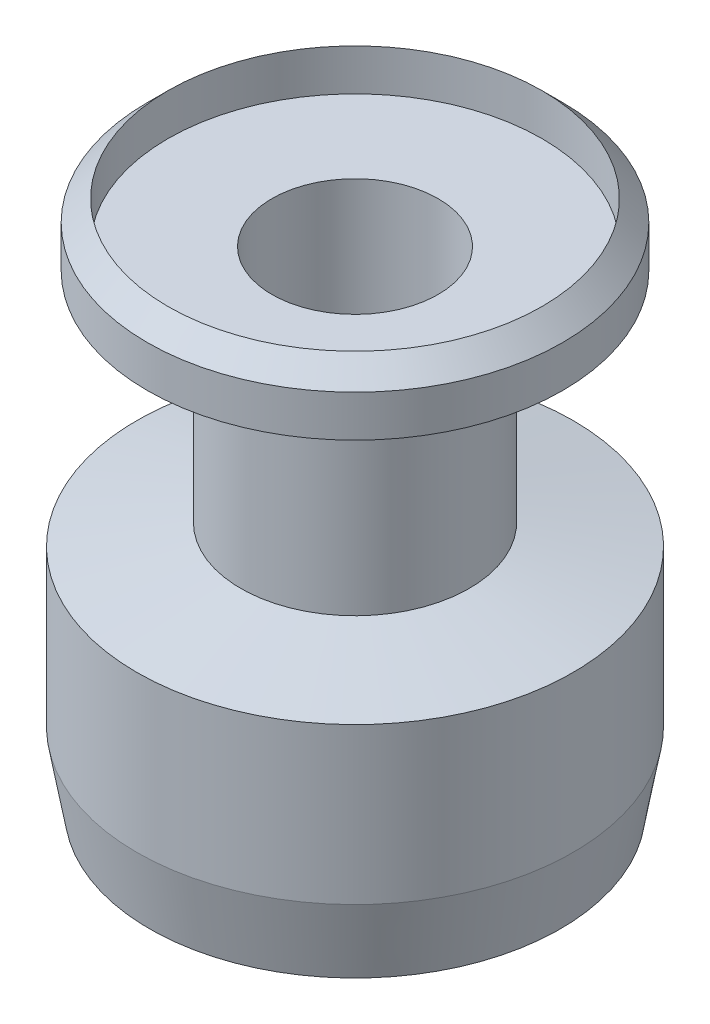
SolidWorks part; units mm, degrees
ref_plane "Front Plane" through (0, 0, 0) normal (0, 0, 1) x (1, 0, 0)
ref_plane "Top Plane" through (0, 0, 0) normal (0, 1, 0) x (1, 0, 0)
ref_plane "Right Plane" through (0, 0, 0) normal (1, 0, 0) x (0, 0, -1)
sketch "Sketch1" plane through (0, 0, 0) normal (0, 0, 1) x (1, 0, 0)
  line L0 (0, 0) -> (0, 51)
  line L2 (20, 49) -> (20, 45)
  line L3 (18, 51) -> (20, 49)
  line L4 (8, 20) -> (8, 31.645)
  line L7 (11, 43) -> (20, 45)
  line L8 (11, 43) -> (11, 24)
  line L12 (11, 24) -> (21, 22)
  line L13 (19, 0) -> (19.7657, 0)
  line L14 (21, 7) -> (21, 22)
  line L15 (19, 0) -> (19, 20)
  line L16 (21, 7) -> (19.7657, 0)
  line L17 (19, 20) -> (8, 20)
  line L18 (8, 0) -> (8, 51) construction
  line L19 (18, 51) -> (18, 47)
  line L20 (18, 47) -> (8, 47)
  line L21 (8, 20) -> (8, 31)
  line L22 (8, 47) -> (8, 37.7344)
  line L23 (8, 35.5) -> (4, 35.5)
  line L24 (4, 35.5) -> (4, 33)
  line L25 (4, 33) -> (2, 33)
  line L26 (2, 33) -> (2, 31)
  line L27 (2, 31) -> (8, 31)
  line L28 (8, 35.5) -> (8, 47)
  dimension "D1" = 8
revolve "Revolve1" add sketch "Sketch1" angle 360 about L0
